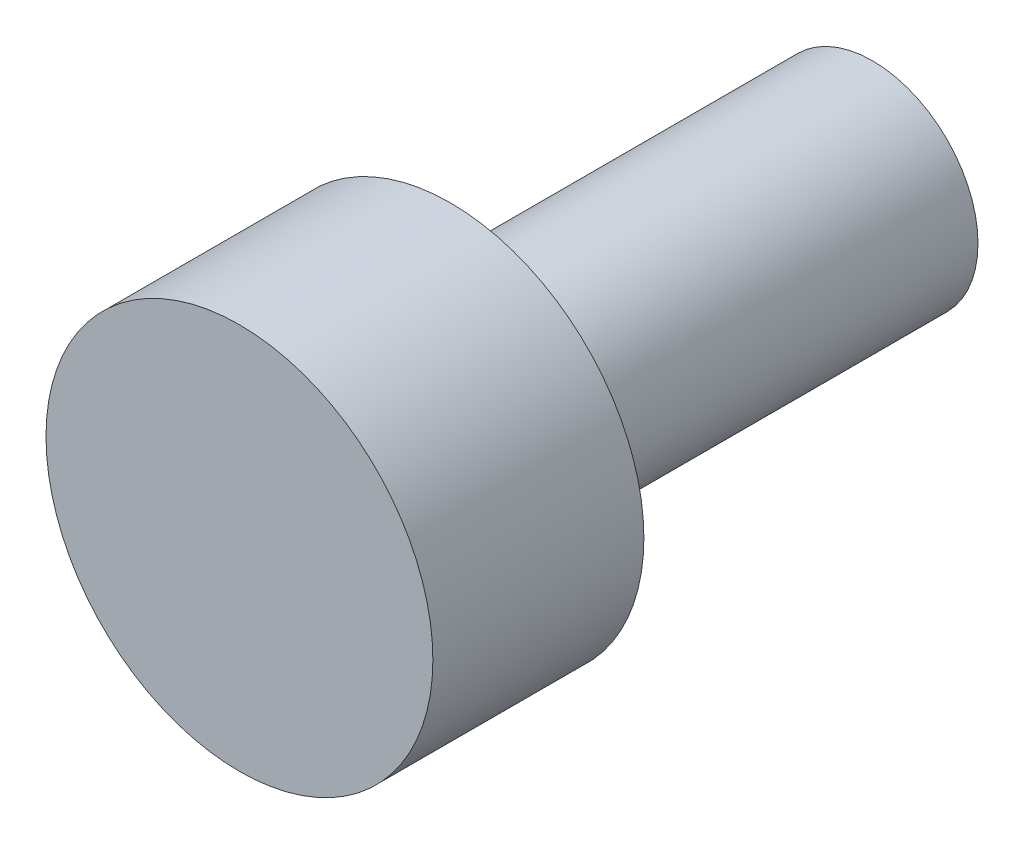
SolidWorks part; units mm, degrees
ref_plane "前视基准面" through (0, 0, 0) normal (0, 0, 1) x (1, 0, 0)
ref_plane "上视基准面" through (0, 0, 0) normal (0, 1, 0) x (1, 0, 0)
ref_plane "右视基准面" through (0, 0, 0) normal (1, 0, 0) x (0, 0, -1)
other "Configuration Table"
sketch "草图1" plane through (0, 0, 0) normal (0, 0, 1) x (1, 0, 0)
  circle A0 centre (0, 0) radius 1.5
extrude "M3杆" add sketch "草图1" along normal blind 6
sketch "草图2" plane through (0, 0, 0) normal (0, 0, 1) x (1, 0, 0)
  circle A0 centre (0, 0) radius 2.75
extrude "螺钉头" add sketch "草图2" along normal blind 3 from offset 6
